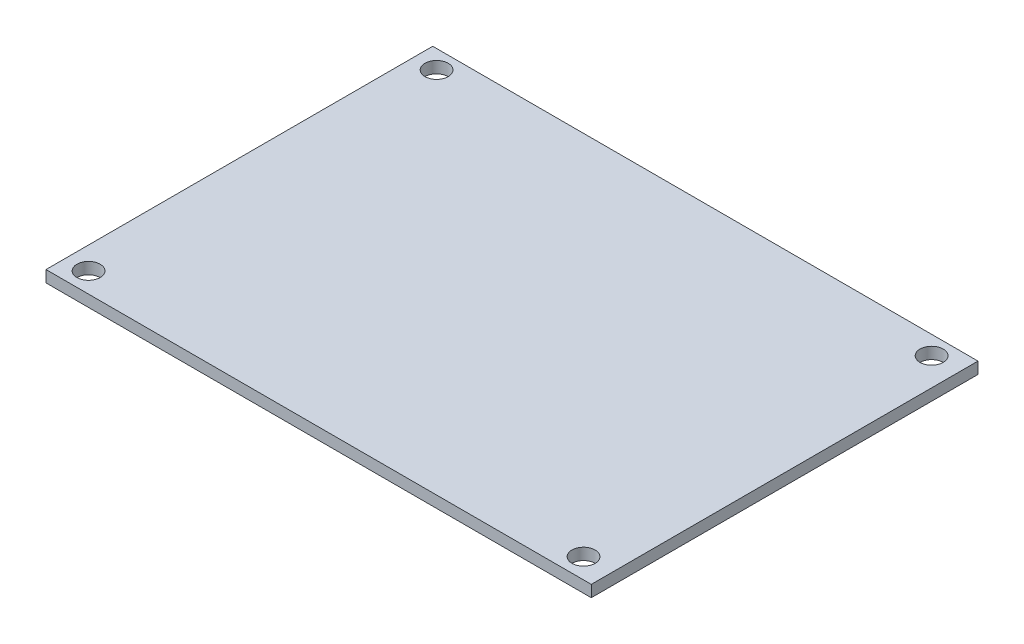
SolidWorks part; units mm, degrees
ref_plane "Plan de face" through (0, 0, 0) normal (0, 0, 1) x (1, 0, 0)
ref_plane "Plan de dessus" through (0, 0, 0) normal (0, 1, 0) x (1, 0, 0)
ref_plane "Plan de droite" through (0, 0, 0) normal (1, 0, 0) x (0, 0, -1)
sketch "Esquisse1" plane through (0, 0, 0) normal (0, 1, 0) x (1, 0, 0)
  line L1 (-35.25, 25) -> (35.25, 25)
  line L2 (-35.25, 25) -> (-35.25, -25)
  line L3 (-35.25, -25) -> (35.25, -25)
  line L4 (35.25, 25) -> (35.25, -25)
  line L5 (-35.25, 25) -> (35.25, -25) construction
  line L6 (-35.25, -25) -> (35.25, 25) construction
  circle A0 centre (-32.35, 22.6) radius 1.5
  circle A4 centre (-32.35, -22.4) radius 1.5
  circle A5 centre (31.65, 22.6) radius 1.5
  circle A6 centre (31.65, -22.4) radius 1.5
  point P0 (0, 0)
  point P14 (0, 0)
  point P15 (0, 0)
  point P16 (0, 0)
  point P17 (0, 0)
  point P18 (0, 0)
  point P19 (0, 0)
  point P20 (32.05, -20.8915)
  point P21 (0, 0)
  point P22 (0, 0)
  point P23 (0, 0)
  point P24 (32.05, -21.0207)
  dimension "D3" = 3
  dimension "D6" = 64
  dimension "D1" = 70.5
  dimension "D2" = 50
  dimension "D4" = 2.4
  dimension "D5" = 2.9
  dimension "D7" = 45
extrude "Boss.-Extru.1" add sketch "Esquisse1" along normal blind 1.5
